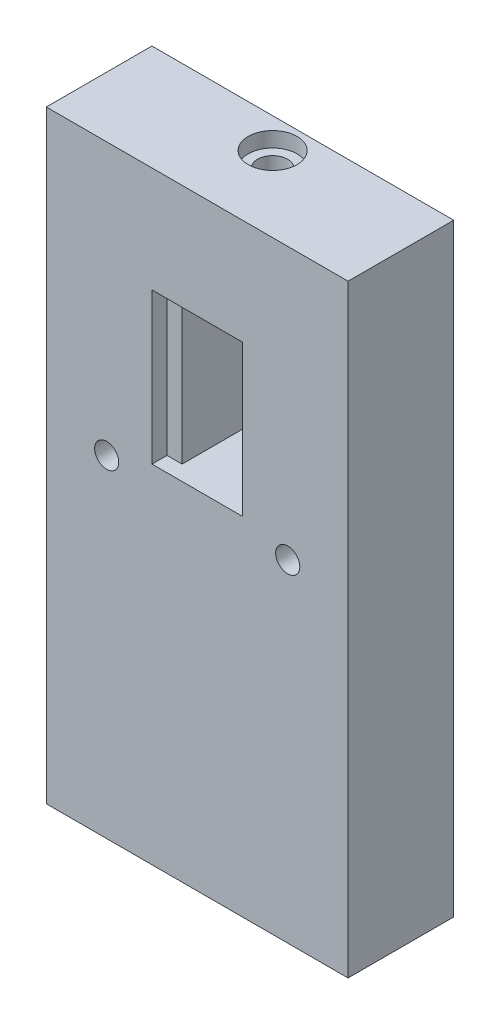
SolidWorks part; units mm, degrees
ref_plane "Front Plane" through (0, 0, 0) normal (0, 0, 1) x (1, 0, 0)
ref_plane "Top Plane" through (0, 0, 0) normal (0, 1, 0) x (1, 0, 0)
ref_plane "Right Plane" through (0, 0, 0) normal (1, 0, 0) x (0, 0, -1)
sketch "Sketch1" plane through (0, 0, 0) normal (0, 0, 1) x (1, 0, 0)
  line L1 (-50, 100) -> (50, 100)
  line L2 (-50, 100) -> (-50, -100)
  line L3 (-50, -100) -> (50, -100)
  line L4 (50, 100) -> (50, -100)
  line L5 (-50, 100) -> (50, -100) construction
  line L6 (-50, -100) -> (50, 100) construction
  point P0 (0, 0)
  dimension "D1" = 100
  dimension "D2" = 200
extrude "Boss-Extrude1" add sketch "Sketch1" along normal blind 35
sketch "Sketch2" plane through (0, 0, 35) normal (0, 0, 1) x (1, 0, 0)
  line L0 (-30, 10) -> (30, 10) construction
  line L1 (0, 0) -> (0, 10) construction
  circle A0 centre (-30, 10) radius 4
  circle A1 centre (30, 10) radius 4
  point P7 (0, 10)
  dimension "D3" = 8
  dimension "D1" = 60
  dimension "D2" = 10
extrude "Cut-Extrude1" cut sketch "Sketch2" against normal blind 30
sketch "Sketch3" plane through (0, 100, 0) normal (0, 1, 0) x (1, 0, 0)
  line L1 (-5, -5) -> (5, -5) construction
  line L2 (-5, -5) -> (-5, -15) construction
  line L3 (-5, -15) -> (5, -15) construction
  line L4 (5, -5) -> (5, -15) construction
  line L5 (0, 0) -> (0, -5) construction
  circle A0 centre (0, -10) radius 5
  dimension "D1" = 10
  dimension "D2" = 10
  dimension "D3" = 5
extrude "Cut-Extrude2" cut sketch "Sketch3" against normal through all
sketch "Sketch4" plane through (0, 0, 0) normal (0, 0, -1) x (-1, 0, 0)
  line L0 (0, 0) -> (0, 40) construction
  line L1 (-10, 65) -> (10, 65)
  line L2 (-10, 65) -> (-10, 15)
  line L3 (-10, 15) -> (10, 15)
  line L4 (10, 65) -> (10, 15)
  line L5 (-10, 65) -> (10, 15) construction
  line L6 (-10, 15) -> (10, 65) construction
  point P0 (0, 40)
  dimension "D1" = 20
  dimension "D2" = 50
  dimension "D3" = 40
extrude "Cut-Extrude3" cut sketch "Sketch4" against normal through all
sketch "Sketch6" plane through (0, 100, 0) normal (0, 1, 0) x (1, 0, 0)
  circle A0 centre (0, -10) radius 8.1
  dimension "D1" = 16.2
extrude "Cut-Extrude4" cut sketch "Sketch6" against normal blind 5
mirror "Mirror1" about plane through (0, 0, 0) normal (0, 1, 0) of "Cut-Extrude4"
sketch "Sketch7" plane through (0, 0, 35) normal (0, 0, 1) x (1, 0, 0)
  line L0 (10, 15) -> (-10, 15) construction
  line L1 (-15, 15) -> (15, 15)
  line L2 (-15, 15) -> (-15, 65)
  line L3 (-15, 65) -> (15, 65)
  line L4 (15, 15) -> (15, 65)
  line L5 (-10, 65) -> (10, 65) construction
  line L6 (-15, 40) -> (-10, 40) construction
  line L7 (-10, 15) -> (-10, 65) construction
  line L9 (10, 65) -> (10, 15) construction
  line L10 (10, 40) -> (15, 40) construction
  dimension "D1" = 5
extrude "Cut-Extrude5" cut sketch "Sketch7" against normal blind 5
